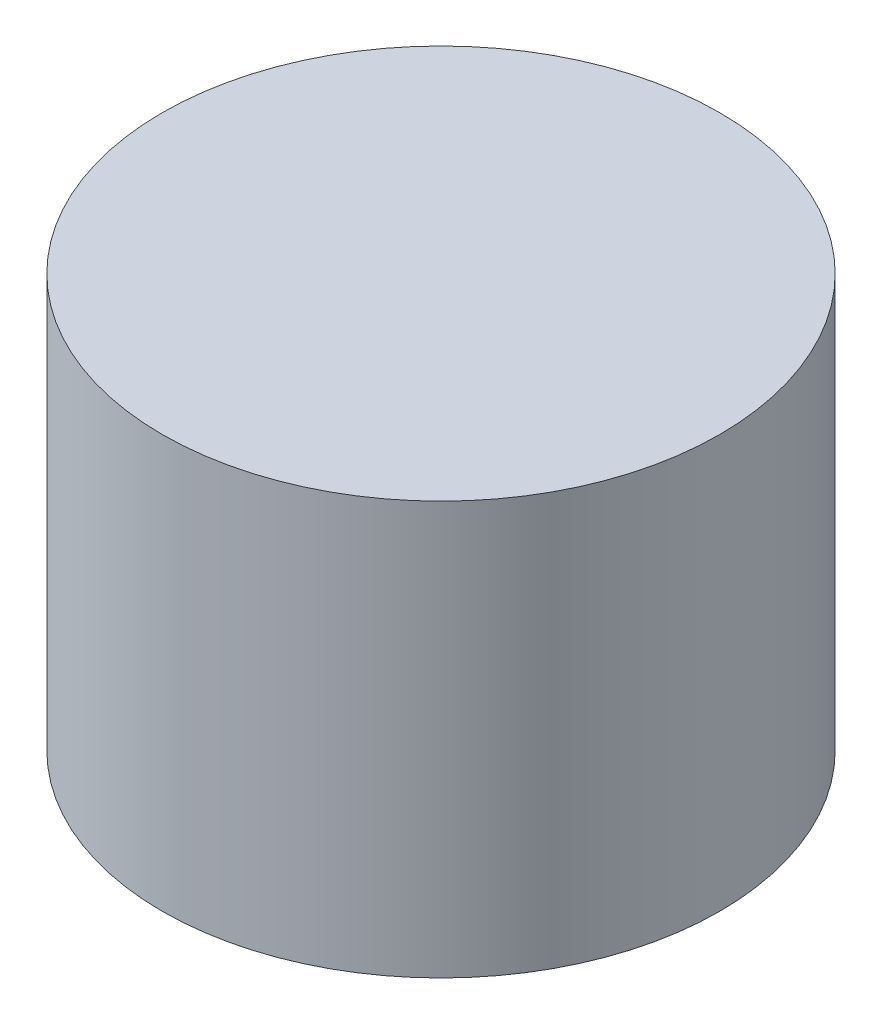
SolidWorks part; units mm, degrees
material "Water"
ref_plane "Front Plane" through (0, 0, 0) normal (0, 0, 1) x (1, 0, 0)
ref_plane "Top Plane" through (0, 0, 0) normal (0, 1, 0) x (1, 0, 0)
ref_plane "Right Plane" through (0, 0, 0) normal (1, 0, 0) x (0, 0, -1)
sketch "Sketch1" plane through (0, 0, 0) normal (0, 1, 0) x (1, 0, 0)
  circle A0 centre (0, 0) radius 13.5
  dimension "D1" = 27
extrude "Boss-Extrude1" add sketch "Sketch1" along normal blind 20
